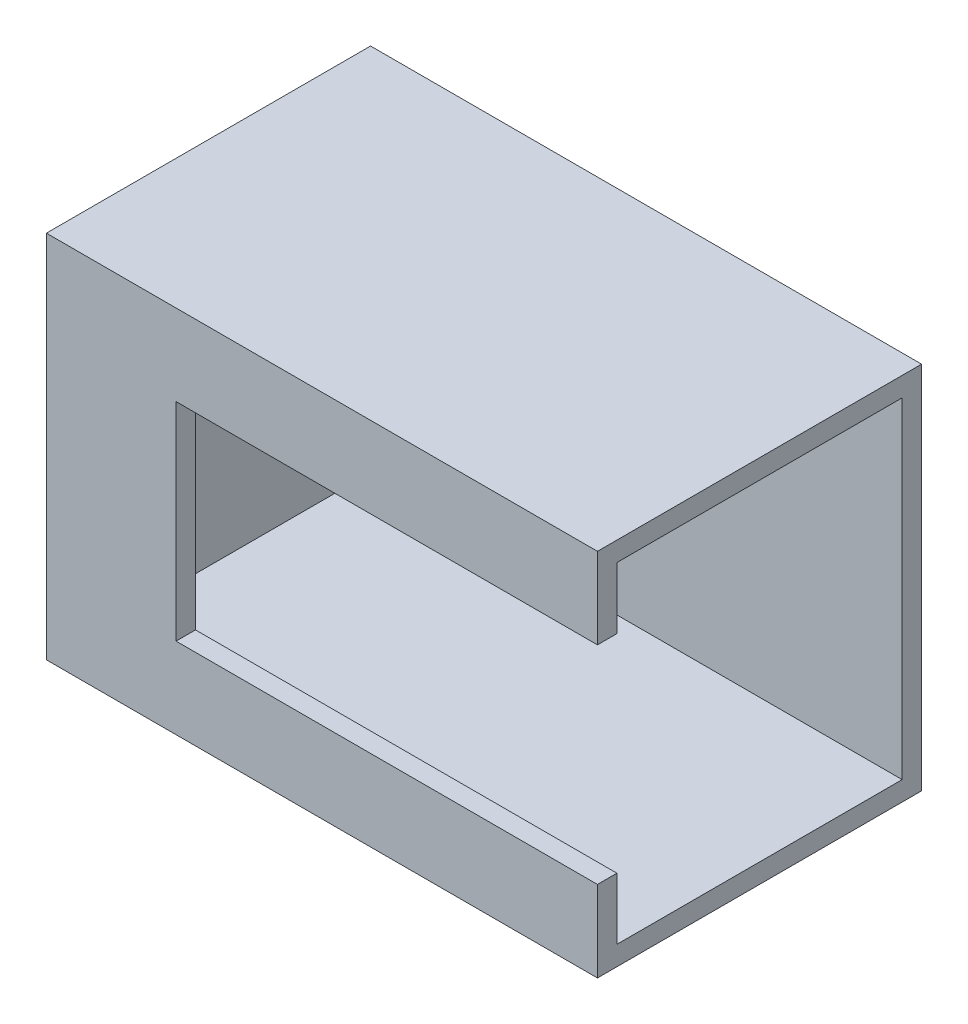
SolidWorks part; units mm, degrees
ref_plane "前视基准面" through (0, 0, 0) normal (0, 0, 1) x (1, 0, 0)
ref_plane "上视基准面" through (0, 0, 0) normal (0, 1, 0) x (1, 0, 0)
ref_plane "右视基准面" through (0, 0, 0) normal (1, 0, 0) x (0, 0, -1)
other "Configuration Table"
sketch "草图1" plane through (0, 0, 0) normal (0, 1, 0) x (1, 0, 0)
  line L1 (-42.5, -25) -> (42.5, -25)
  line L2 (-42.5, -25) -> (-42.5, 25)
  line L3 (-42.5, 25) -> (42.5, 25)
  line L4 (42.5, -25) -> (42.5, 25)
  line L5 (-42.5, -25) -> (42.5, 25) construction
  line L6 (-42.5, 25) -> (42.5, -25) construction
  point P0 (0, 0)
  dimension "D1" = 85
  dimension "D2" = 50
extrude "凸台-拉伸1" add sketch "草图1" along normal blind 57
sketch "草图3" plane through (42.5, 0, 0) normal (1, 0, 0) x (0, 0, -1)
  line L0 (0, 0) -> (0, 57)
  line L1 (-25, 57) -> (25, 57) construction
  line L2 (-25, 57) -> (-25, 0) construction
  line L3 (-22, 3) -> (22, 3)
  line L4 (-22, 3) -> (-22, 54)
  line L5 (-22, 54) -> (22, 54)
  line L6 (22, 3) -> (22, 54)
  line L7 (-22, 3) -> (22, 54) construction
  line L8 (-22, 54) -> (22, 3) construction
  line L9 (-25, 0) -> (25, 0) construction
  line L10 (25, 57) -> (25, 0) construction
  point P5 (0, 28.5)
  dimension "D1" = 3
  dimension "D2" = 3
  dimension "D3" = 3
  dimension "D4" = 3
extrude "切除-拉伸2" cut sketch "草图3" against normal blind 82 contours L5 L4 L3 L0 | L3 L6 L5 L0
sketch "草图4" plane through (0, 0, 25) normal (0, 0, 1) x (1, 0, 0)
  line L0 (42.5, 57) -> (42.5, 0) construction
  line L1 (42.5, 44.5) -> (-22.5, 44.5)
  line L2 (42.5, 44.5) -> (42.5, 12.5)
  line L3 (42.5, 12.5) -> (-22.5, 12.5)
  line L4 (-22.5, 44.5) -> (-22.5, 12.5)
  line L5 (-42.5, 57) -> (42.5, 57) construction
  line L6 (-42.5, 0) -> (42.5, 0) construction
  line L7 (-42.5, 57) -> (-42.5, 0) construction
  dimension "D1" = 12.5
  dimension "D2" = 12.5
  dimension "D3" = 20
extrude "切除-拉伸4" cut sketch "草图4" against normal up to next
